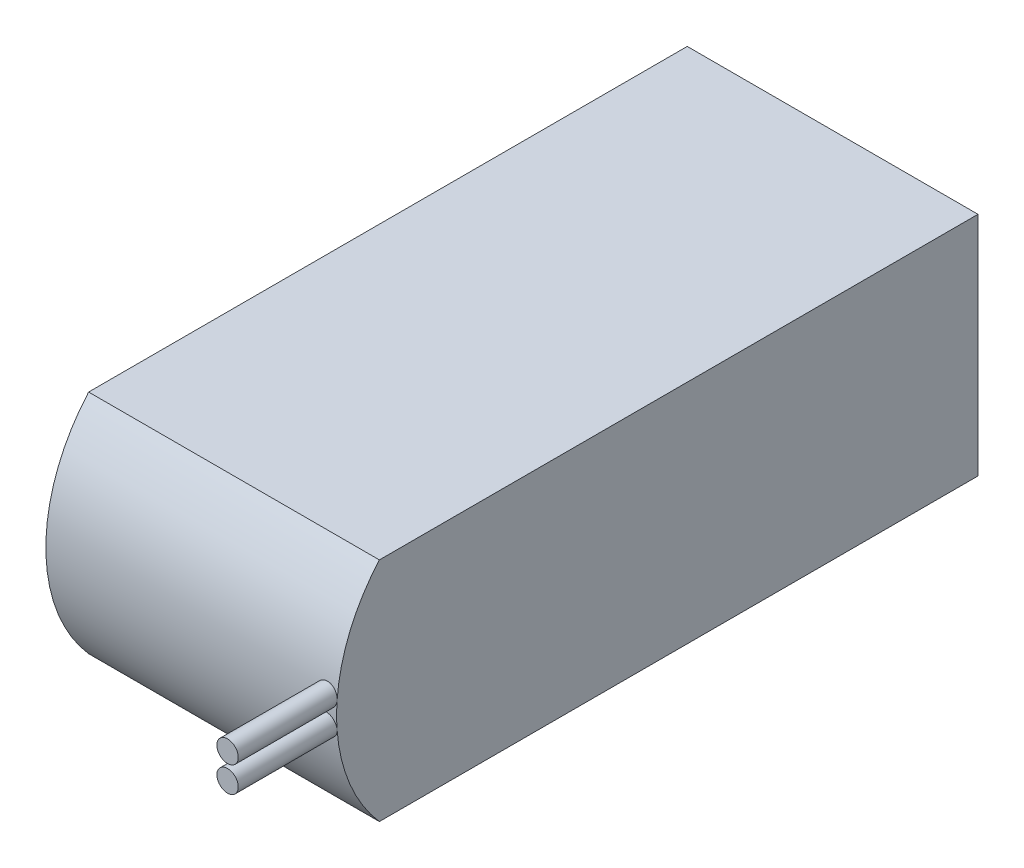
SolidWorks part; units mm, degrees
ref_plane "Plan de face" through (0, 0, 0) normal (0, 0, 1) x (1, 0, 0)
ref_plane "Plan de dessus" through (0, 0, 0) normal (0, 1, 0) x (1, 0, 0)
ref_plane "Plan de droite" through (0, 0, 0) normal (1, 0, 0) x (0, 0, -1)
sketch "Esquisse1" plane through (0, 0, 0) normal (0, 0, 1) x (1, 0, 0)
  line L1 (0, 0) -> (68, 0)
  line L2 (0, 0) -> (0, 53)
  line L3 (0, 53) -> (68, 53)
  line L4 (68, 0) -> (68, 53)
  dimension "D1" = 53
  dimension "D2" = 68
extrude "Boss.-Extru.1" add sketch "Esquisse1" along normal blind 140
sketch "Esquisse2" plane through (68, 0, 0) normal (1, 0, 0) x (0, 0, -1)
  line L0 (-140, 0) -> (-140, 53) construction
  line L1 (-140, 53) -> (-140, 0)
  arc A0 (-140, 53) -> (-140, 0) centre (-109.8875, 26.5) ccw
  point P7 (-150, 26.5)
  dimension "D1" = 10
extrude "Boss.-Extru.2" add sketch "Esquisse2" against normal up to vertex (68 mm away) up to point (0, 53, 140)
sketch "Esquisse3" plane through (0, 0, 0) normal (0, 0, -1) x (-1, 0, 0)
  line L0 (-68, 0) -> (-68, 53) construction
  line L1 (-65.5, 29.5) -> (-65.5, 23.5) construction
  line L2 (-68, 26.5) -> (0, 26.5) construction
  line L3 (0, 53) -> (0, 0) construction
  circle A0 centre (-65.5, 29.5) radius 2.5
  circle A1 centre (-65.5, 23.5) radius 2.5
  point P9 (-65.5, 23.5)
  dimension "D1" = 5
  dimension "D2" = 3
  dimension "D3" = 3
extrude "Boss.-Extru.3" add sketch "Esquisse3" against normal blind 173
